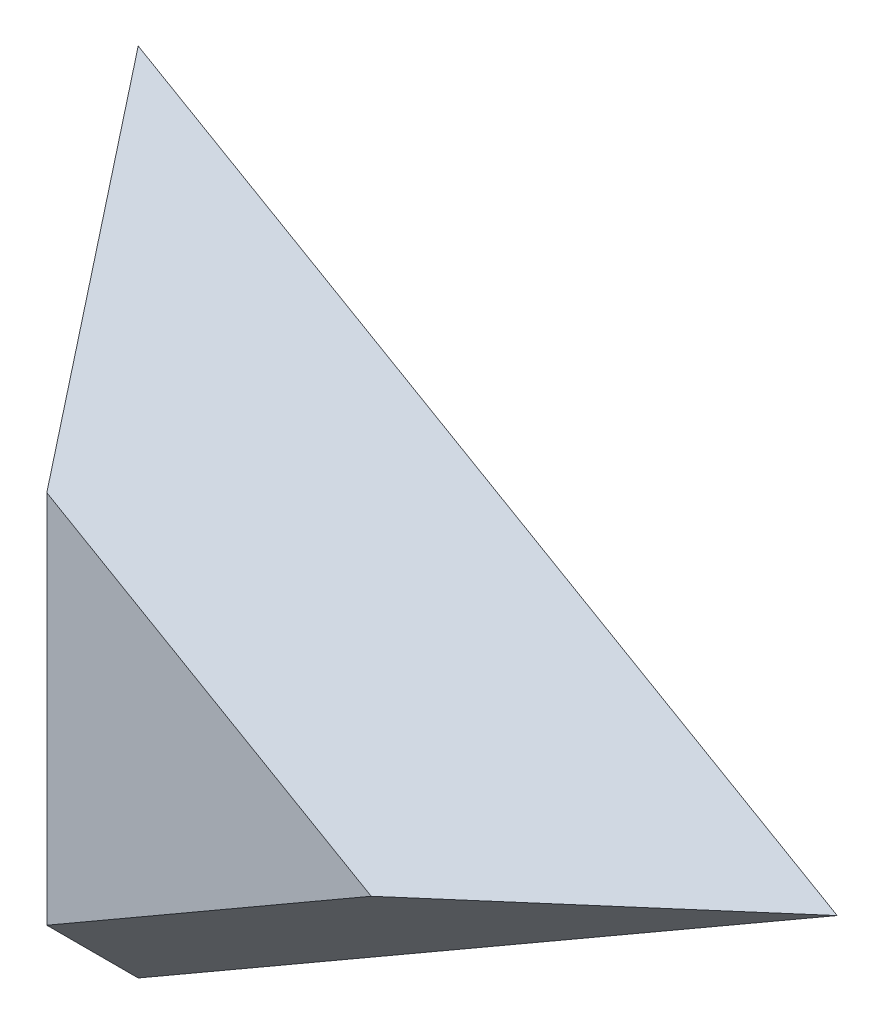
SolidWorks part; units mm, degrees
ref_plane "前视基准面" through (0, 0, 0) normal (0, 0, 1) x (1, 0, 0)
ref_plane "上视基准面" through (0, 0, 0) normal (0, 1, 0) x (1, 0, 0)
ref_plane "右视基准面" through (0, 0, 0) normal (1, 0, 0) x (0, 0, -1)
other "Configuration Table"
sketch "草图1" plane through (0, 0, 0) normal (0, 0, 1) x (1, 0, 0)
  line L1 (30, 0) -> (-15, 25.9808)
  line L2 (-15, 25.9808) -> (-15, -25.9808)
  line L3 (-15, -25.9808) -> (30, 0)
  circle A0 centre (0, 0) radius 15 construction
extrude "凸台-拉伸2" add sketch "草图1" along normal mid plane 30
draft "拔模3" type of draft neutral plane draft angle 30 faces to draft 3 face at (7.5, -12.9904, 0) face at (-15, 0, 0) face at (7.5, 12.9904, 0) neutral plane through (0, 0, 15) neutral plane normal (0, 0, 1) parameters "D1"=30
